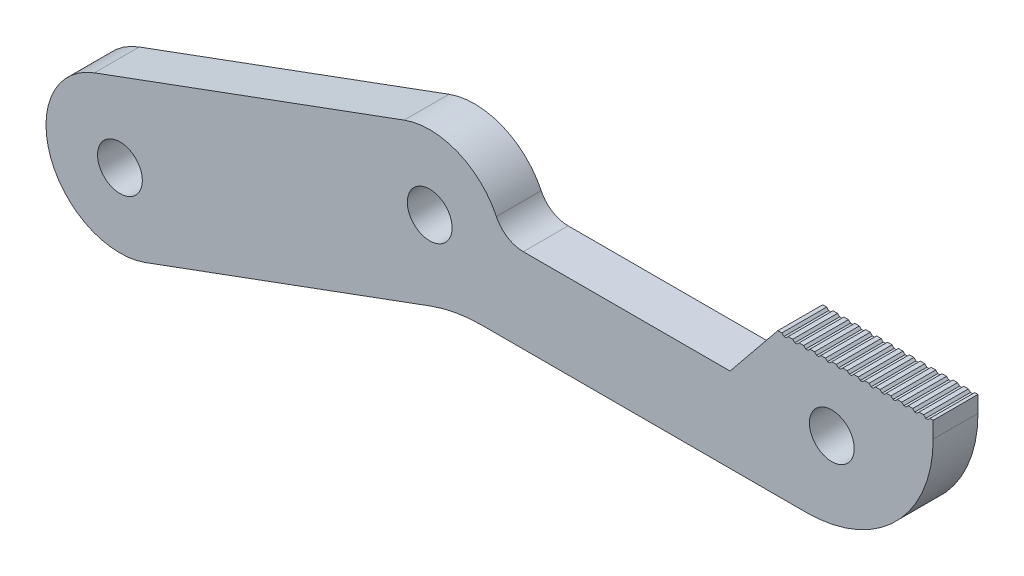
SolidWorks part; units mm, degrees
ref_plane "Front Plane" through (0, 0, 0) normal (0, 0, 1) x (1, 0, 0)
ref_plane "Top Plane" through (0, 0, 0) normal (0, 1, 0) x (1, 0, 0)
ref_plane "Right Plane" through (0, 0, 0) normal (1, 0, 0) x (0, 0, -1)
sketch "Sketch2" plane through (0, 0, 0) normal (0, 0, 1) x (1, 0, 0)
  line L0 (4.6456, 1.709) -> (1.4919, 10.282) construction
  line L1 (0, 0) -> (30.0324, 11.0479) construction
  line L2 (4.6456, 1.709) -> (7.7083, -6.6165) construction
  line L3 (25.3868, 9.3389) -> (28.4555, 0.997) construction
  line L4 (25.3868, 9.3389) -> (22.4415, 17.3453) construction
  line L5 (2.9367, 6.3546) -> (23.6778, 13.9845)
  line L6 (6.3546, -2.9367) -> (25.4243, 4.0784)
  line L7 (28.8767, 4.6933) -> (50.5957, 4.6933)
  line L8 (45.4957, 10.3433) -> (31.6538, 10.3433)
  line L9 (45.4957, 2.0222) -> (45.4957, 14.9789) construction
  line L10 (59.0957, 14.2889) -> (58.8777, 14.2889)
  line L11 (45.4957, 10.3433) -> (48.6957, 14.2889)
  line L12 (59.0957, 13.1933) -> (59.0957, 14.2889)
  line L13 (48.9643, 14.2889) -> (49.1018, 14.1514)
  line L14 (49.1018, 14.1514) -> (49.2502, 14.1514)
  line L15 (49.2502, 14.1514) -> (49.3877, 14.2889)
  line L16 (49.6943, 14.2889) -> (49.8318, 14.1514)
  line L17 (49.8318, 14.1514) -> (49.9802, 14.1514)
  line L18 (49.9802, 14.1514) -> (50.1177, 14.2889)
  line L19 (50.4243, 14.2889) -> (50.5618, 14.1514)
  line L20 (50.5618, 14.1514) -> (50.7102, 14.1514)
  line L21 (50.7102, 14.1514) -> (50.8477, 14.2889)
  line L22 (51.1543, 14.2889) -> (51.2918, 14.1514)
  line L23 (51.2918, 14.1514) -> (51.4402, 14.1514)
  line L24 (51.4402, 14.1514) -> (51.5777, 14.2889)
  line L25 (51.8843, 14.2889) -> (52.0218, 14.1514)
  line L26 (52.0218, 14.1514) -> (52.1702, 14.1514)
  line L27 (52.1702, 14.1514) -> (52.3077, 14.2889)
  line L28 (52.6143, 14.2889) -> (52.7518, 14.1514)
  line L29 (52.7518, 14.1514) -> (52.9002, 14.1514)
  line L30 (52.9002, 14.1514) -> (53.0377, 14.2889)
  line L31 (53.3443, 14.2889) -> (53.4818, 14.1514)
  line L32 (53.4818, 14.1514) -> (53.6302, 14.1514)
  line L33 (53.6302, 14.1514) -> (53.7677, 14.2889)
  line L34 (54.0743, 14.2889) -> (54.2118, 14.1514)
  line L35 (54.2118, 14.1514) -> (54.3602, 14.1514)
  line L36 (54.3602, 14.1514) -> (54.4977, 14.2889)
  line L37 (54.8043, 14.2889) -> (54.9418, 14.1514)
  line L38 (54.9418, 14.1514) -> (55.0902, 14.1514)
  line L39 (55.0902, 14.1514) -> (55.2277, 14.2889)
  line L40 (55.5343, 14.2889) -> (55.6718, 14.1514)
  line L41 (55.6718, 14.1514) -> (55.8202, 14.1514)
  line L42 (55.8202, 14.1514) -> (55.9577, 14.2889)
  line L43 (56.2643, 14.2889) -> (56.4018, 14.1514)
  line L44 (56.4018, 14.1514) -> (56.5502, 14.1514)
  line L45 (56.5502, 14.1514) -> (56.6877, 14.2889)
  line L46 (56.9943, 14.2889) -> (57.1318, 14.1514)
  line L47 (57.1318, 14.1514) -> (57.2802, 14.1514)
  line L48 (57.2802, 14.1514) -> (57.4177, 14.2889)
  line L49 (57.7243, 14.2889) -> (57.8618, 14.1514)
  line L50 (57.8618, 14.1514) -> (58.0102, 14.1514)
  line L51 (58.0102, 14.1514) -> (58.1477, 14.2889)
  line L52 (58.4543, 14.2889) -> (58.5918, 14.1514)
  line L53 (58.5918, 14.1514) -> (58.7402, 14.1514)
  line L54 (58.7402, 14.1514) -> (58.8777, 14.2889)
  line L55 (48.9643, 14.2889) -> (48.6957, 14.2889)
  line L56 (49.6943, 14.2889) -> (49.3877, 14.2889)
  line L57 (50.4243, 14.2889) -> (50.1177, 14.2889)
  line L58 (51.1543, 14.2889) -> (50.8477, 14.2889)
  line L59 (51.8843, 14.2889) -> (51.5777, 14.2889)
  line L60 (52.6143, 14.2889) -> (52.3077, 14.2889)
  line L61 (53.3443, 14.2889) -> (53.0377, 14.2889)
  line L62 (54.0743, 14.2889) -> (53.7677, 14.2889)
  line L63 (54.8043, 14.2889) -> (54.4977, 14.2889)
  line L64 (55.5343, 14.2889) -> (55.2277, 14.2889)
  line L65 (56.2643, 14.2889) -> (55.9577, 14.2889)
  line L66 (56.9943, 14.2889) -> (56.6877, 14.2889)
  line L67 (57.7243, 14.2889) -> (57.4177, 14.2889)
  line L68 (58.4543, 14.2889) -> (58.1477, 14.2889)
  arc A0 (29.8504, 11.4787) -> (23.6778, 13.9845) centre (25.3868, 9.3389) ccw
  arc A1 (2.9367, 6.3546) -> (6.3546, -2.9367) centre (4.6456, 1.709) ccw
  circle A2 centre (4.6456, 1.709) radius 1.5
  circle A3 centre (25.3868, 9.3389) radius 1.5
  arc A4 (50.5957, 4.6933) -> (59.0957, 13.1933) centre (50.5957, 13.1933) ccw
  arc A5 (28.8767, 4.6933) -> (25.4243, 4.0784) centre (28.8767, -5.3067) ccw
  arc A6 (31.6538, 10.3433) -> (29.8504, 11.4787) centre (31.6538, 12.3433) cw
  circle A7 centre (52.3077, 9.9948) radius 1.5
  point P11 (25.3868, 9.3389)
  point P24 (59.0957, 4.6933)
  dimension "D1" = 9.9
  dimension "D2" = 9.9
  dimension "D4" = 2
  dimension "D6" = 8.5
  dimension "D8" = 10
  dimension "D3" = 32
  dimension "D5" = 5.65
  dimension "D7" = 10.4
  dimension "D9" = 14
extrude "Boss-Extrude1" add sketch "Sketch2" along normal blind 3 contours L5 A0 A6 L8 L11 L55 L13 L14 L15 L56 L16 L17 L18 L57 L19 L20 L21 L58 L22 L23 L24 L59 L25 L26 L27 L60 L28 L29 L30 L61 L31 L32 L33 L62 L34 L35 L36 L63 L37 L38 L39 L64 L40 L41 L42 L65 L43 L44 L45 L66 L46 L47 L48 L67 L49 L50 L51 L68 L52 L53 L54 L10 L12 A4 L7 A5 L6 A1
